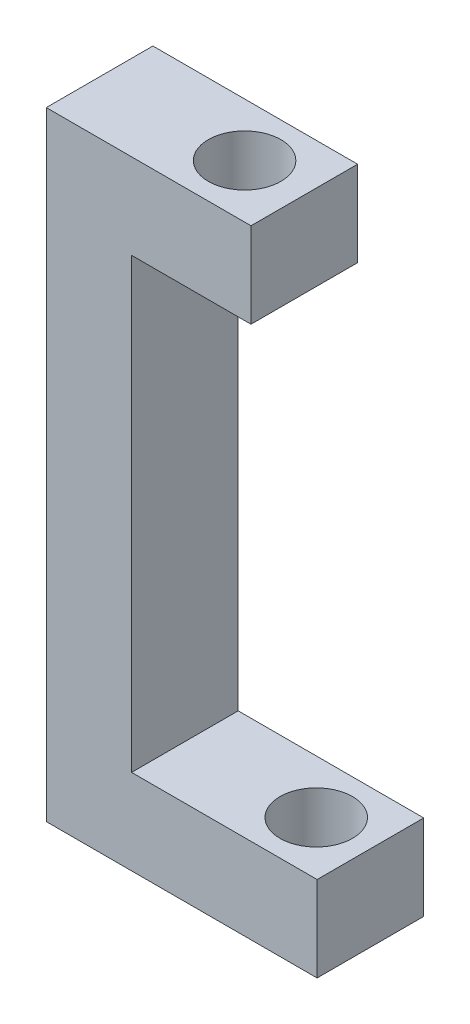
SolidWorks part; units mm, degrees
material "Filme de alta densidade PE"
ref_plane "Plano frontal" through (0, 0, 0) normal (0, 0, 1) x (1, 0, 0)
ref_plane "Plano superior" through (0, 0, 0) normal (0, 1, 0) x (1, 0, 0)
ref_plane "Plano direito" through (0, 0, 0) normal (1, 0, 0) x (0, 0, -1)
sketch "Esboço1" plane through (0, 0, 0) normal (0, 0, 1) x (1, 0, 0)
  line L0 (12.7, -29) -> (0, -29)
  line L1 (0, -29) -> (0, 0)
  line L2 (0, 0) -> (9.6, 0)
  line L4 (9.6, 0) -> (9.6, -4)
  line L5 (9.6, -4) -> (4, -4)
  line L6 (4, -4) -> (4, -25)
  line L7 (4, -25) -> (12.7, -25)
  line L8 (12.7, -25) -> (12.7, -29)
  dimension "D1" = 4
  dimension "D2" = 4
  dimension "D3" = 4
  dimension "D4" = 12.7
  dimension "D5" = 29
  dimension "D6" = 5.6
extrude "Ressalto-extrusão1" add sketch "Esboço1" along normal blind 5
hole_wizard "Furo com folga de M32" positions "Esboço2" profile "Esboço3" hole size "M3" standard "Ansi Metric"
sketch "Esboço2" plane through (0, -25, 0) normal (0, 1, 0) x (1, 0, 0)
  line L0 (-980.0626, -2.5) -> (49019.9374, -2.5) construction
  line L1 (12.7, -5) -> (12.7, 0) construction
  point P0 (10.16, -2.5)
  point P8 (12.7, -2.5)
  dimension "D1" = 2.54
sketch "Esboço3" plane through (10.16, -25, 2.5) normal (1, 0, 0) x (0, 0, 1)
  line L0 (0, 0) -> (0, 4)
  line L1 (0, 4) -> (1.7, 4)
  line L2 (1.7, 4) -> (1.7, 0)
  line L5 (1.7, 0) -> (0, 0)
  line L11 (0, -6.35) -> (0, 107.95) construction
  dimension "Thru Hole Dia." = 3.4
  dimension "Thru Hole Depth" = 4
hole_wizard "Furo com folga de M31" positions "Esboço4" profile "Esboço5" hole size "M3" standard "Ansi Metric"
sketch "Esboço4" plane through (0, 0, 0) normal (0, 1, 0) x (1, 0, 0)
  line L0 (9.6, -5) -> (9.6, 0) construction
  point P0 (6.8, -2.5)
  point P5 (9.6, -2.5)
  dimension "D1" = 2.8
sketch "Esboço5" plane through (6.8, 0, 2.5) normal (1, 0, 0) x (0, 0, 1)
  line L0 (0, 0) -> (0, 12.2715)
  line L1 (0, 12.2715) -> (1.7, 11.25)
  line L2 (1.7, 11.25) -> (1.7, 0)
  line L5 (1.7, 0) -> (0, 0)
  line L10 (0, 12.2715) -> (-1.7, 11.25) construction
  line L11 (0, -6.35) -> (0, 107.95) construction
  dimension "Hole Dia." = 3.4
  dimension "Hole Depth" = 11.25
  dimension "Drill Angle" = 118
